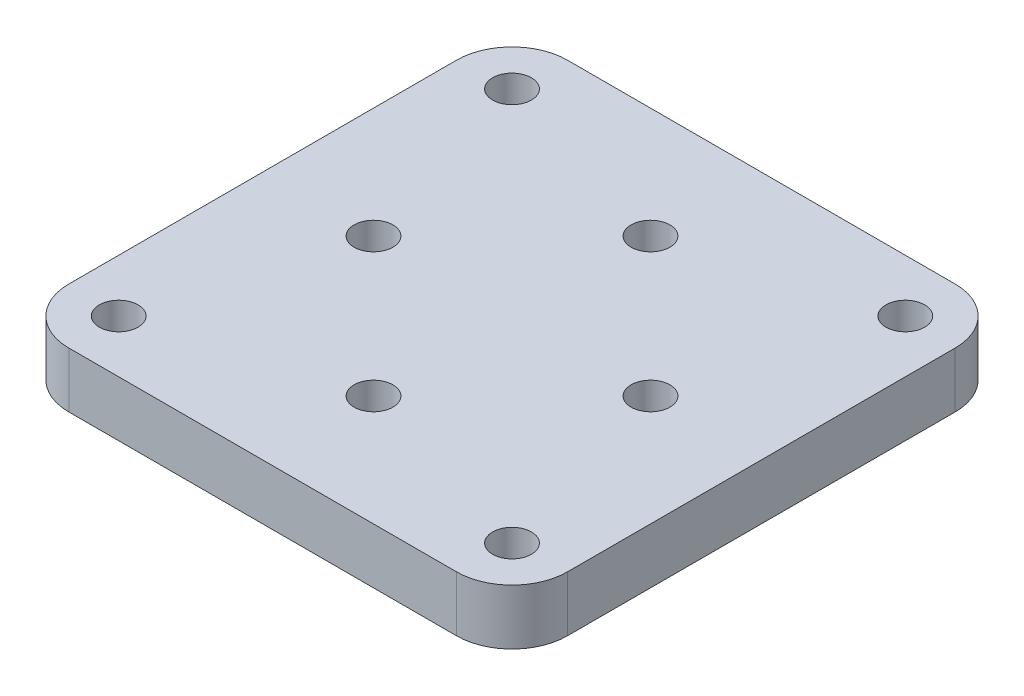
SolidWorks part; units mm, degrees
ref_plane "Front Plane" through (0, 0, 0) normal (0, 0, 1) x (1, 0, 0)
ref_plane "Top Plane" through (0, 0, 0) normal (0, 1, 0) x (1, 0, 0)
ref_plane "Right Plane" through (0, 0, 0) normal (1, 0, 0) x (0, 0, -1)
sketch "Sketch1" plane through (0, 0, 0) normal (0, 1, 0) x (1, 0, 0)
  line L1 (-45, 45) -> (45, 45)
  line L2 (-45, 45) -> (-45, -45)
  line L3 (-45, -45) -> (45, -45)
  line L4 (45, 45) -> (45, -45)
  line L5 (-45, 45) -> (45, -45) construction
  line L6 (-45, -45) -> (45, 45) construction
  point P0 (0, 0)
  dimension "D1" = 90
extrude "Boss-Extrude1" add sketch "Sketch1" along normal blind 10
sketch "Sketch2" plane through (0, 10, 0) normal (0, 1, 0) x (1, 0, 0)
  line L0 (45, 45) -> (-45, 45) construction
  line L2 (-45, 45) -> (-45, -45) construction
  line L4 (45, -45) -> (45, 45) construction
  line L5 (-45, -45) -> (45, -45) construction
  circle A1 centre (0, 25) radius 3
  circle A2 centre (-25, 0) radius 3
  circle A3 centre (25, 0) radius 3
  circle A4 centre (0, -25) radius 3
  circle A5 centre (-35.5, 35.5) radius 3
  circle A6 centre (35.5, 35.5) radius 3
  circle A7 centre (35.5, -35.5) radius 3
  circle A8 centre (-35.5, -35.5) radius 3
  point P27 (0, 0)
  dimension "D1" = 6
  dimension "D2" = 6
  dimension "D3" = 6
  dimension "D4" = 6
  dimension "D5" = 9.5
  dimension "D7" = 6
  dimension "D9" = 6
  dimension "D10" = 6
  dimension "D12" = 6
  dimension "D6" = 9.5
  dimension "D8" = 9.5
  dimension "D11" = 9.5
  dimension "D13" = 9.5
  dimension "D14" = 9.5
  dimension "D15" = 9.5
  dimension "D16" = 9.5
hole_wizard "M6 Clearance Hole1" positions "Sketch3" profile "Sketch4" hole size "M6" standard "ISO" end condition through all
sketch "Sketch3" plane through (0, 10, 0) normal (0, 1, 0) x (1, 0, 0)
  circle A0 centre (0, 0) radius 25
  point P5 (0, 25)
  point P7 (25, 0)
  point P9 (0, -25)
  point P11 (-25, 0)
  dimension "D1" = 50
sketch "Sketch4" plane through (-25, 10, 0) normal (1, 0, 0) x (0, 0, 1)
  line L0 (0, 0) -> (0, 10)
  line L1 (0, 10) -> (3.5, 10)
  line L2 (3.5, 10) -> (3.5, 0)
  line L5 (3.5, 0) -> (0, 0)
  line L11 (0, -6.35) -> (0, 107.95) construction
  dimension "Thru Hole Dia." = 7
  dimension "Thru Hole Depth" = 10
hole_wizard "M6 Clearance Hole2" positions "3DSketch1" profile "Sketch5" hole size "M6" standard "ISO" end condition through all
sketch3d "3DSketch1"
  point P0 (-35.5, 10, -35.5)
  point P3 (-35.5, 10, 35.5)
  point P6 (35.5, 10, -35.5)
  point P9 (35.5, 10, 35.5)
sketch "Sketch5" plane through (-35.5, 10, -35.5) normal (1, 0, 0) x (0, 0, 1)
  line L0 (0, 0) -> (0, 10)
  line L1 (0, 10) -> (3.5, 10)
  line L2 (3.5, 10) -> (3.5, 0)
  line L5 (3.5, 0) -> (0, 0)
  line L11 (0, -6.35) -> (0, 107.95) construction
  dimension "Thru Hole Dia." = 7
  dimension "Thru Hole Depth" = 10
fillet "Fillet1" radius 10 4 edges at (45, 5, -45) (-45, 5, -45) (45, 5, 45) (-45, 5, 45)
